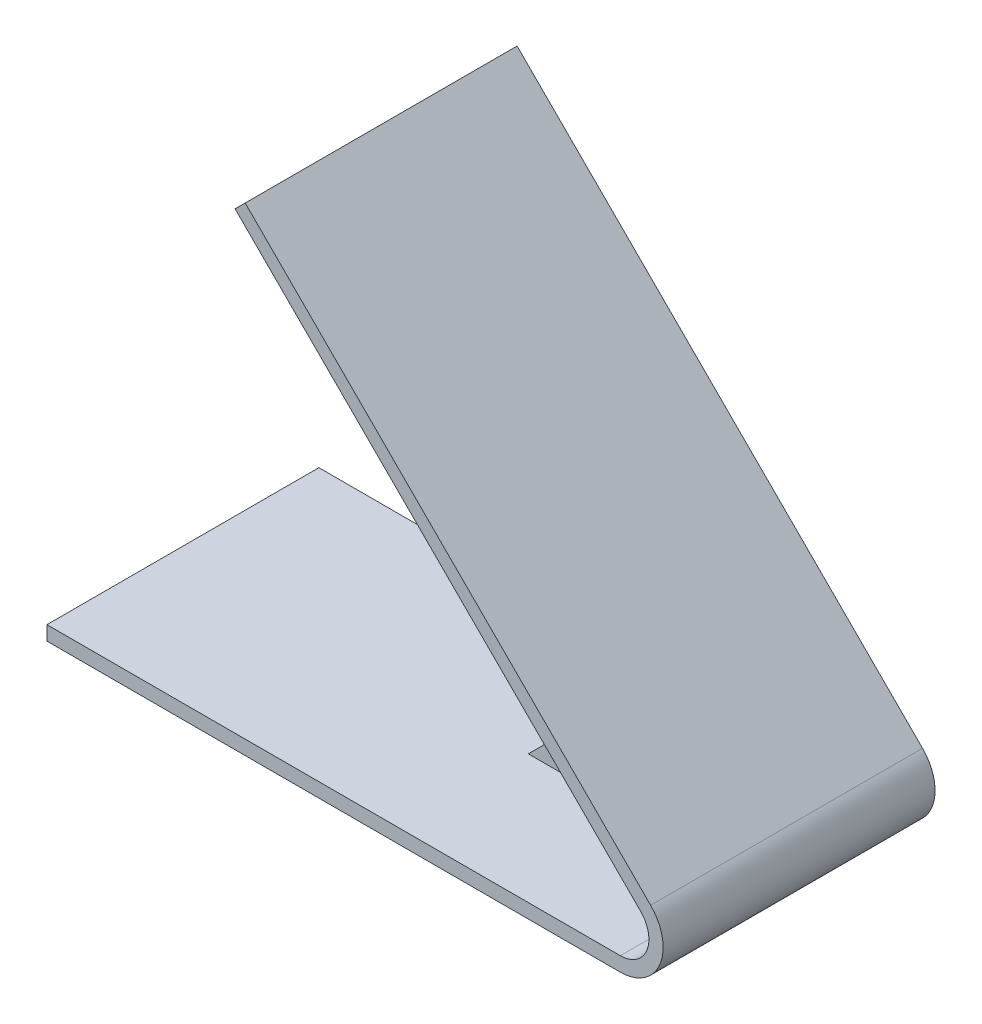
SolidWorks part; units mm, degrees
ref_plane "Alzado" through (0, 0, 0) normal (0, 0, 1) x (1, 0, 0)
ref_plane "Planta" through (0, 0, 0) normal (0, 1, 0) x (1, 0, 0)
ref_plane "Vista lateral" through (0, 0, 0) normal (1, 0, 0) x (0, 0, -1)
sketch "Croquis1" plane through (0, 0, 0) normal (0, 0, 1) x (1, 0, 0)
  line L0 (-6.8284, 6.8284) -> (-63.6396, 63.6396)
  line L1 (-9.6569, 0) -> (-90, 0)
  line L2 (-9.6569, -2) -> (-90, -2)
  line L3 (-5.4142, 8.2426) -> (-62.2254, 65.0538)
  line L4 (-62.2254, 65.0538) -> (-63.6396, 63.6396)
  line L5 (-90, -2) -> (-90, 0)
  arc A0 (-6.8284, 6.8284) -> (-9.6569, 0) centre (-9.6569, 4) cw
  arc A1 (-5.4142, 8.2426) -> (-9.6569, -2) centre (-9.6569, 4) cw
  point P7 (0, 0)
  dimension "D3" = 4
  dimension "D1" = 45
  dimension "D2" = 90
  dimension "D4" = 2
extrude "Saliente-Extruir1" add sketch "Croquis1" along normal blind 38.1
ref_plane "Plano4" through (0, 0, 19.05) normal (0, 0, 1) x (1, 0, 0)
sketch "Croquis3" plane through (0, 0, 19.05) normal (0, 0, 1) x (1, 0, 0)
  line L0 (-40.5976, 0) -> (-20.2988, 20.2988)
  line L1 (-9.6569, 0) -> (-90, 0) construction
  line L2 (-63.6396, 63.6396) -> (-6.8284, 6.8284) construction
  line L3 (-20.2988, 20.2988) -> (-6.8284, 6.8284)
  line L4 (-6.8284, 6.8284) -> (-13.6569, 0)
  line L5 (-13.6569, 0) -> (-40.5976, 0)
  dimension "D1" = 19.05
extrude "Saliente-Extruir2" add sketch "Croquis3" along normal mid plane 2
